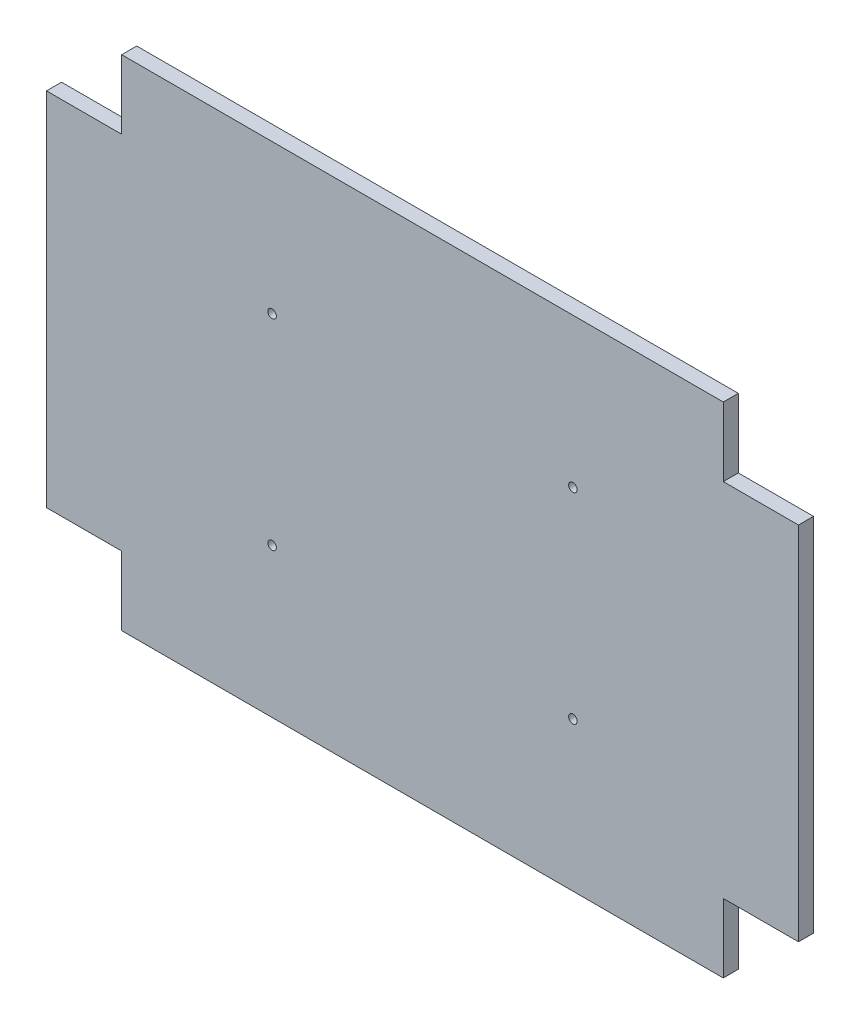
SolidWorks part; units mm, degrees
ref_plane "Front Plane" through (0, 0, 0) normal (0, 0, 1) x (1, 0, 0)
ref_plane "Top Plane" through (0, 0, 0) normal (0, 1, 0) x (1, 0, 0)
ref_plane "Right Plane" through (0, 0, 0) normal (1, 0, 0) x (0, 0, -1)
sketch "Sketch1" plane through (0, 0, 0) normal (0, 0, 1) x (1, 0, 0)
  line L0 (120, 72) -> (150, 72)
  line L1 (-120, -99.5) -> (120, -99.5)
  line L2 (-150, -72) -> (-150, 72)
  line L3 (-120, 99.5) -> (120, 99.5)
  line L4 (150, -72) -> (150, 72)
  line L9 (-150, 72) -> (-120, 72)
  line L10 (-120, 99.5) -> (-120, 72)
  line L14 (120, 99.5) -> (120, 72)
  line L15 (150, -72) -> (120, -72)
  line L16 (120, -99.5) -> (120, -72)
  line L17 (-150, -72) -> (-120, -72)
  line L18 (-120, -99.5) -> (-120, -72)
  point P0 (0, 0)
  point P12 (-8.0027, 5.3085)
  point P15 (-8.0027, 5.3085)
  dimension "D1" = 199
  dimension "D2" = 27.5
  dimension "D3" = 30
  dimension "D4" = 27.5
  dimension "D5" = 300
  dimension "D6" = 30
  dimension "D7" = 144
  dimension "D8" = 99.5
  dimension "D9" = 150
  dimension "D10" = 150
  dimension "D11" = 99.5
  dimension "D12" = 199
  dimension "D13" = 27.5
  dimension "D14" = 72
  dimension "D15" = 120
  dimension "D16" = 72
  dimension "D18" = 120
extrude "Boss-Extrude1" add sketch "Sketch1" along normal blind 6
sketch "Sketch2" plane through (0, 0, 6) normal (0, 0, 1) x (1, 0, 0)
  line L1 (-60, -40) -> (60, -40)
  line L2 (-60, -40) -> (-60, 40)
  line L3 (-60, 40) -> (60, 40)
  line L4 (60, -40) -> (60, 40)
  line L5 (-60, -40) -> (60, 40) construction
  line L6 (-60, 40) -> (60, -40) construction
  point P0 (0, 0)
  dimension "D1" = 120
  dimension "D2" = 80
hole_wizard "M3 Clearance Hole1" positions "3DSketch1" profile "Sketch3" hole size "M3" standard "ISO" end condition through all
sketch3d "3DSketch1"
  point P0 (-60, 40, 6)
  point P3 (-60, -40, 6)
  point P6 (60, -40, 6)
  point P9 (60, 40, 6)
sketch "Sketch3" plane through (-60, 40, 6) normal (1, 0, 0) x (0, -1, 0)
  line L0 (0, 0) -> (0, 6)
  line L1 (0, 6) -> (1.7, 6)
  line L2 (1.7, 6) -> (1.7, 0)
  line L5 (1.7, 0) -> (0, 0)
  line L11 (0, -6.35) -> (0, 107.95) construction
  dimension "Thru Hole Dia." = 3.4
  dimension "Thru Hole Depth" = 6
